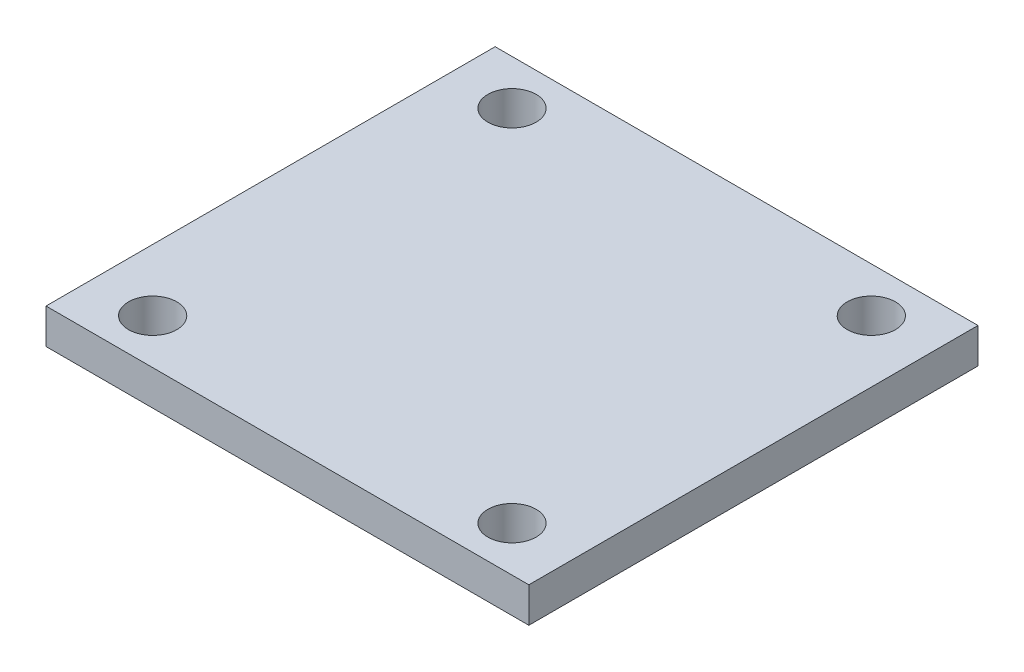
SolidWorks part; units mm, degrees
material "6061 Alloy"
ref_plane "Front Plane" through (0, 0, 0) normal (0, 0, 1) x (1, 0, 0)
ref_plane "Top Plane" through (0, 0, 0) normal (0, 1, 0) x (1, 0, 0)
ref_plane "Right Plane" through (0, 0, 0) normal (1, 0, 0) x (0, 0, -1)
sketch "Sketch1" plane through (0, 0, 0) normal (0, 1, 0) x (1, 0, 0)
  line L1 (-21.5, -20) -> (21.5, -20)
  line L2 (-21.5, -20) -> (-21.5, 20)
  line L3 (-21.5, 20) -> (21.5, 20)
  line L4 (21.5, -20) -> (21.5, 20)
  line L5 (-21.5, -20) -> (21.5, 20) construction
  line L6 (-21.5, 20) -> (21.5, -20) construction
  point P0 (0, 0)
  dimension "D1" = 43
  dimension "D2" = 20
extrude "Boss-Extrude1" add sketch "Sketch1" along normal blind 3.125
sketch "Sketch2" plane through (0, 3.125, 0) normal (0, 1, 0) x (1, 0, 0)
  line L0 (21.5, 20) -> (-21.5, 20) construction
  line L1 (-21.5, 20) -> (-21.5, -20) construction
  point P0 (-16, 16)
  point P3 (16, 16)
  point P8 (16, -16)
  point P9 (-16, -16)
  dimension "D1" = 4
  dimension "D2" = 5.5
  dimension "D5" = 36
  dimension "D6" = 37.5
  dimension "D3" = 2
  dimension "D4" = 2
hole_wizard "M4 Clearance Hole1" positions "Sketch2" profile "Sketch3" hole size "M4" standard "ANSI Metric" end condition through all
sketch "Sketch3" plane through (-16, 3.125, -16) normal (1, 0, 0) x (0, 0, 1)
  line L0 (0, 0) -> (0, 3.125)
  line L1 (0, 3.125) -> (2.15, 3.125)
  line L2 (2.15, 3.125) -> (2.15, 0)
  line L5 (2.15, 0) -> (0, 0)
  line L11 (0, -6.35) -> (0, 107.95) construction
  dimension "Thru Hole Dia." = 4.3
  dimension "Thru Hole Depth" = 3.125
sketch "Sketch4" [suppressed] plane through (0, 3.125, 0) normal (0, 1, 0) x (1, 0, 0)
  point P0 (0, 0)
hole_wizard "M4x0.7 Tapped Hole1" [suppressed] positions "Sketch4" profile "Sketch5" tap size "M4x0.7" standard "ANSI Metric"
sketch "Sketch5" plane through (0, 3.125, 0) normal (1, 0, 0) x (0, 0, 1)
  line L0 (0, 0) -> (0, 3.125)
  line L1 (0, 3.125) -> (1.65, 3.125)
  line L2 (1.65, 3.125) -> (1.65, 0)
  line L5 (1.65, 0) -> (0, 0)
  line L11 (0, -6.35) -> (0, 107.95) construction
  dimension "Thru Tap Drill Dia." = 3.3
  dimension "Thru Tap Drill Depth" = 3.125
cosmetic thread "Hole Thread1" [suppressed] parameters "D2"=4
